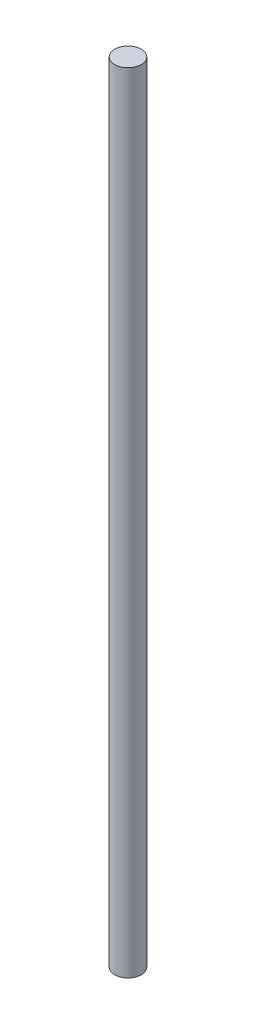
SolidWorks part; units mm, degrees
ref_plane "Front Plane" through (0, 0, 0) normal (0, 0, 1) x (1, 0, 0)
ref_plane "Top Plane" through (0, 0, 0) normal (0, 1, 0) x (1, 0, 0)
ref_plane "Right Plane" through (0, 0, 0) normal (1, 0, 0) x (0, 0, -1)
sketch "Sketch1" plane through (0, 0, 0) normal (0, 1, 0) x (1, 0, 0)
  circle A0 centre (0, 0) radius 0.675
  dimension "D1" = 1.35
extrude "Boss-Extrude1" add sketch "Sketch1" along normal blind 40
